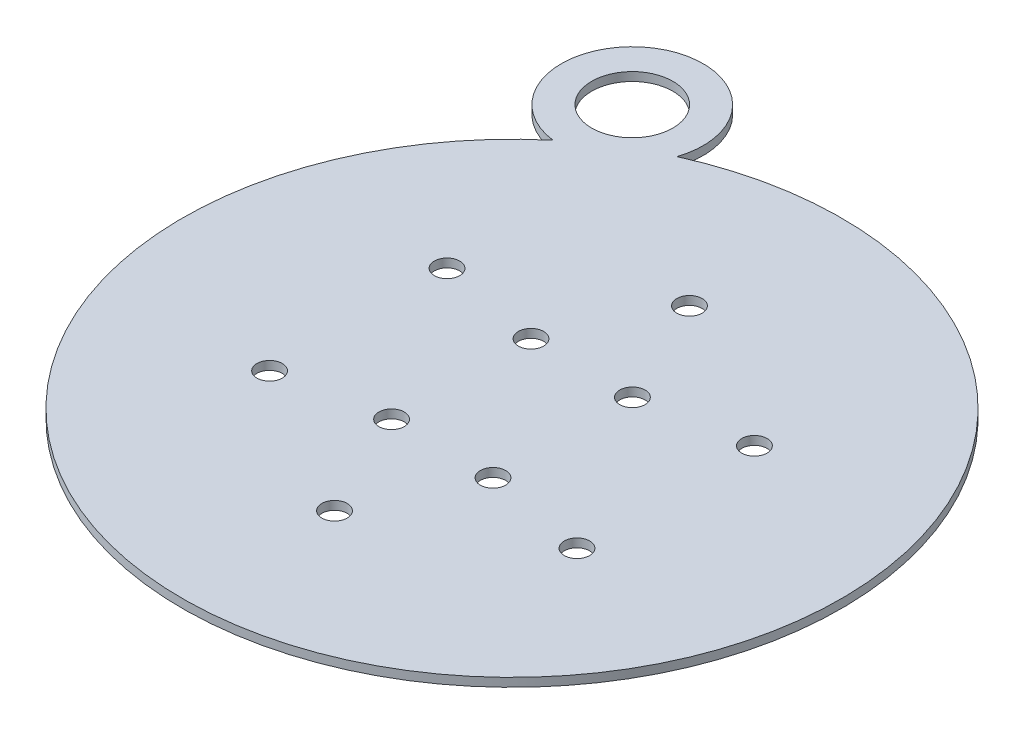
SolidWorks part; units mm, degrees
ref_plane "Front Plane" through (0, 0, 0) normal (0, 0, 1) x (1, 0, 0)
ref_plane "Top Plane" through (0, 0, 0) normal (0, 1, 0) x (1, 0, 0)
ref_plane "Right Plane" through (0, 0, 0) normal (1, 0, 0) x (0, 0, -1)
sketch "Sketch1" plane through (0, 0, 0) normal (0, 1, 0) x (1, 0, 0)
  line L0 (0, 9.3311) -> (0, -58.8842) construction
  line L1 (-10, 13.75) -> (10, 13.75)
  line L2 (-10, 13.75) -> (-10, -13.75)
  line L3 (-10, -13.75) -> (10, -13.75)
  line L4 (10, 13.75) -> (10, -13.75)
  line L5 (-10, 13.75) -> (10, -13.75) construction
  line L6 (-10, -13.75) -> (10, 13.75) construction
  circle A0 centre (-10, 13.75) radius 2.5
  circle A1 centre (10, 13.75) radius 2.5
  circle A2 centre (10, -13.75) radius 2.5
  circle A3 centre (-10, -13.75) radius 2.5
  circle A4 centre (0, 0) radius 150
  circle A5 centre (0, 0) radius 35
  circle A6 centre (0, 35) radius 2.5
  circle A7 centre (30.3109, 17.5) radius 2.5
  circle A8 centre (30.3109, -17.5) radius 2.5
  circle A9 centre (0, -35) radius 2.5
  circle A10 centre (-30.3109, -17.5) radius 2.5
  circle A11 centre (-30.3109, 17.5) radius 2.5
  circle A12 centre (0, 0) radius 65
  circle A13 centre (0, -560) radius 625
  circle A14 centre (-40, 63.7187) radius 8
  circle A15 centre (-40, 63.7187) radius 14
  point P0 (0, 0)
  point P27 (0, 0)
  dimension "D3" = 5
  dimension "D4" = 300
  dimension "D5" = 70
  dimension "D6" = 5
  dimension "D8" = 130
  dimension "D9" = 1250
  dimension "D10" = 16
  dimension "D12" = 6
  dimension "D1" = 20
  dimension "D2" = 27.5
  dimension "D11" = 80
  dimension "D7" = 6
extrude "Boss-Extrude1" add sketch "Sketch1" along normal blind 1.7 contours A3 L3 A2 L4 A1 L1 A0 L2 | A11 A5 A10 A9 A8 A7 A6 A3 L2 A0 L1 A1 L4 A2 L3 | A15 A12 A11 A5 A6 A7 A8 A9 A10 | A13 A15 A14 | A12 A15 | A12 A15 A13 A14
